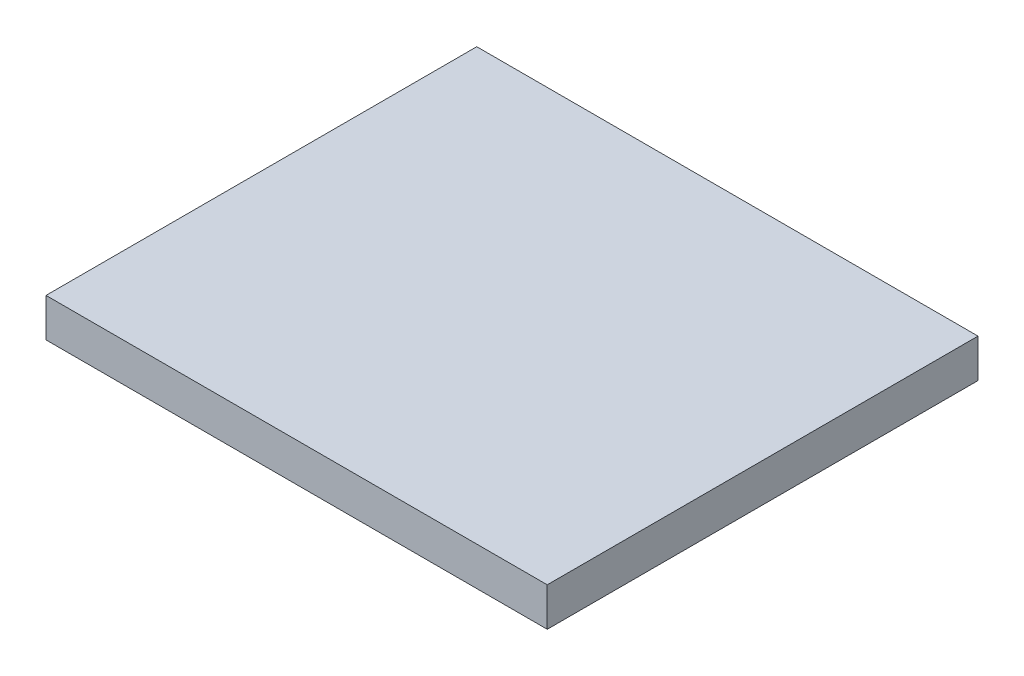
SolidWorks part; units mm, degrees
ref_plane "Front" through (0, 0, 0) normal (0, 0, 1) x (1, 0, 0)
ref_plane "Top" through (0, 0, 0) normal (0, 1, 0) x (1, 0, 0)
ref_plane "Right" through (0, 0, 0) normal (1, 0, 0) x (0, 0, -1)
sketch "Sketch1" plane through (0, 0, 0) normal (0, 1, 0) x (1, 0, 0)
  line L1 (0, 0) -> (65.024, 0)
  line L2 (0, 0) -> (0, 55.88)
  line L3 (0, 55.88) -> (65.024, 55.88)
  line L4 (65.024, 0) -> (65.024, 55.88)
  dimension "D1" = 55.88
  dimension "D2" = 65.024
extrude "Boss-Extrude1" add sketch "Sketch1" along normal blind 5
